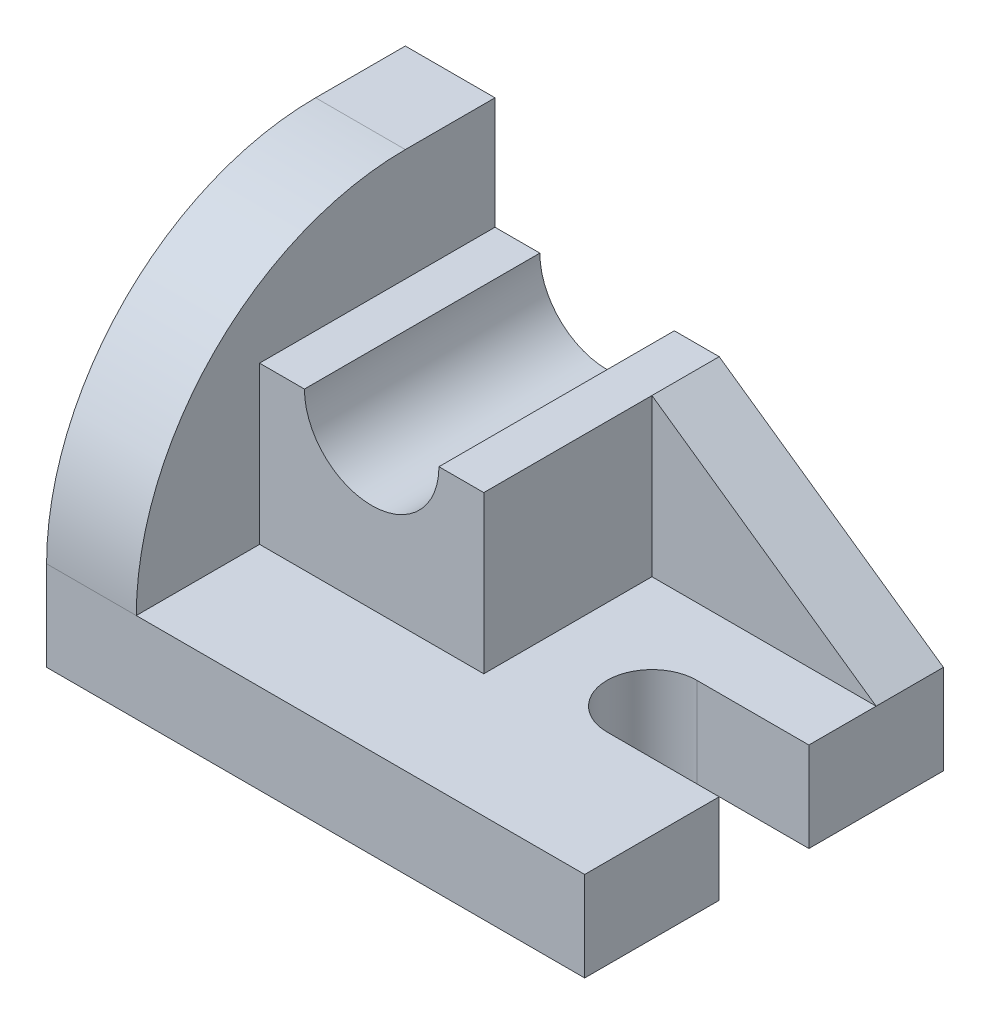
SolidWorks part; units mm, degrees
ref_plane "Front Plane" through (0, 0, 0) normal (0, 0, 1) x (1, 0, 0)
ref_plane "Top Plane" through (0, 0, 0) normal (0, 1, 0) x (1, 0, 0)
ref_plane "Right Plane" through (0, 0, 0) normal (1, 0, 0) x (0, 0, -1)
sketch "Sketch1" plane through (0, 0, 0) normal (0, 1, 0) x (1, 0, 0)
  line L0 (48, 0) -> (28, 0) construction
  line L1 (-48, 32) -> (48, 32)
  line L2 (-48, 32) -> (-48, -32)
  line L3 (-48, -32) -> (48, -32)
  line L4 (48, 32) -> (48, -32)
  line L5 (-48, 32) -> (48, -32) construction
  line L6 (-48, -32) -> (48, 32) construction
  line L7 (48, -8) -> (28, -8)
  line L8 (48, 8) -> (28, 8)
  arc A0 (48, -8) -> (48, 8) centre (48, 0) ccw
  arc A1 (28, 8) -> (28, -8) centre (28, 0) ccw
  point P0 (0, 0)
  point P8 (38, 0)
  dimension "D4" = 8
  dimension "D1" = 96
  dimension "D2" = 64
  dimension "D3" = 20
  dimension "D5" = 24
extrude "Boss-Extrude6" add sketch "Sketch1" along normal blind 16 contours A1 L8 L4 L1 L2 L3 L7
sketch "Sketch2" plane through (0, 0, 32) normal (0, 0, 1) x (1, 0, 0)
  line L1 (-48, 16) -> (-32, 16)
  line L2 (-48, 16) -> (-48, 64)
  line L3 (-48, 64) -> (-32, 64)
  line L4 (-32, 16) -> (-32, 64)
  dimension "D1" = 16
  dimension "D2" = 48
extrude "Boss-Extrude7" add sketch "Sketch2" against normal blind 64
fillet "Fillet2" radius 48 1 edges at (-40, 64, 32)
sketch "Sketch3" plane through (-32, 0, 0) normal (1, 0, 0) x (0, 0, -1)
  line L1 (32, 16) -> (-10, 16)
  line L2 (32, 16) -> (32, 44)
  line L3 (32, 44) -> (-10, 44)
  line L4 (-10, 16) -> (-10, 44)
  dimension "D1" = 42
  dimension "D2" = 28
extrude "Boss-Extrude8" add sketch "Sketch3" along normal blind 40 contours L2 L1 L4 L3
sketch "Sketch4" plane through (0, 0, 10) normal (0, 0, 1) x (1, 0, 0)
  line L0 (8, 44) -> (-32, 44) construction
  circle A0 centre (-12, 44) radius 12
  dimension "D1" = 24
extrude "Cut-Extrude2" cut sketch "Sketch4" against normal blind 69 contours A0
sketch "Sketch5" plane through (0, 0, -32) normal (0, 0, -1) x (-1, 0, 0)
  line L0 (-8, 44) -> (-48, 16)
  line L10 (0, 44) -> (-8, 44)
  line L11 (-8, 44) -> (-8, 16)
  line L12 (-8, 16) -> (-48, 16)
  line L13 (-48, 16) -> (-48, 0)
  line L14 (-48, 0) -> (48, 0)
  line L15 (48, 0) -> (48, 64)
  line L16 (48, 64) -> (32, 64)
  line L17 (32, 64) -> (32, 44)
  line L18 (32, 44) -> (24, 44)
  line L20 (-8, 44) -> (-8, 16)
  line L21 (-8, 16) -> (-48, 16)
  arc A1 (0, 44) -> (24, 44) centre (12, 44) ccw
  dimension "D1" = 0
extrude "Boss-Extrude9" add sketch "Sketch5" against normal blind 12
